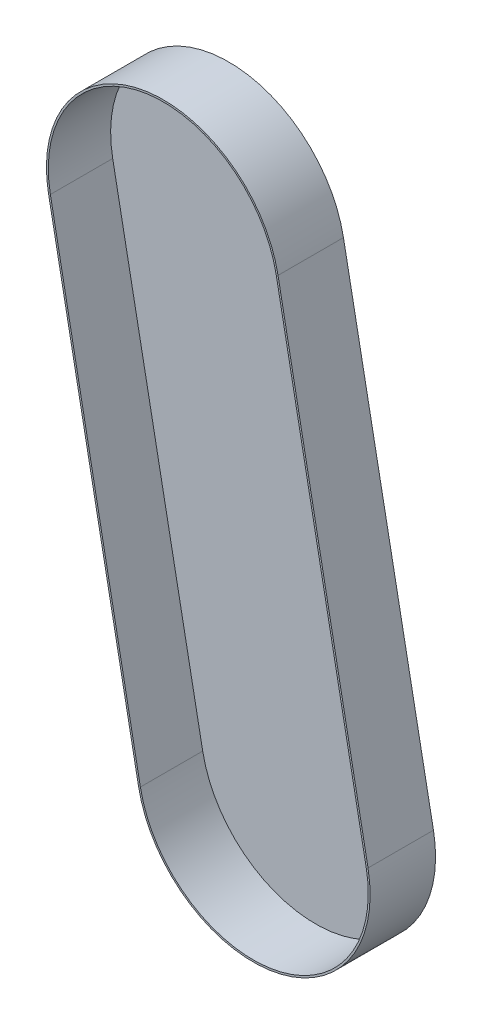
SolidWorks part; units mm, degrees
ref_plane "Front Plane" through (0, 0, 0) normal (0, 0, 1) x (1, 0, 0)
ref_plane "Top Plane" through (0, 0, 0) normal (0, 1, 0) x (1, 0, 0)
ref_plane "Right Plane" through (0, 0, 0) normal (1, 0, 0) x (0, 0, -1)
sketch "Sketch1" plane through (0, 0, 0) normal (0, 0, 1) x (1, 0, 0)
  line L0 (-24.7972, 233.6633) -> (32.9658, -66.856)
  line L1 (-172.1008, 205.3499) -> (-114.3378, -95.1694)
  arc A0 (-24.7972, 233.6633) -> (-172.1008, 205.3499) centre (-98.449, 219.5066) ccw
  arc A1 (-114.3378, -95.1694) -> (32.9658, -66.856) centre (-40.686, -81.0127) ccw
  dimension "D1" = 150
  dimension "D2" = 150
extrude "Boss-Extrude1" add sketch "Sketch1" along normal blind 2
sketch "Sketch2" plane through (0, 0, 2) normal (0, 0, 1) x (1, 0, 0)
  line L0 (-24.7972, 233.6633) -> (32.9658, -66.856)
  line L1 (-172.1008, 205.3499) -> (-114.3378, -95.1694)
  line L2 (-25.9756, 233.4368) -> (31.7874, -67.0826)
  line L3 (-170.9224, 205.5765) -> (-113.1594, -94.9429)
  arc A0 (-24.7972, 233.6633) -> (-172.1008, 205.3499) centre (-98.449, 219.5066) ccw
  arc A1 (-114.3378, -95.1694) -> (32.9658, -66.856) centre (-40.686, -81.0127) ccw
  arc A2 (-113.1594, -94.9429) -> (31.7874, -67.0826) centre (-40.686, -81.0127) ccw
  arc A3 (-25.9756, 233.4368) -> (-170.9224, 205.5765) centre (-98.449, 219.5066) ccw
  dimension "D1" = 150
  dimension "D2" = 150
  dimension "D3" = 1.2
extrude "Boss-Extrude2" add sketch "Sketch2" along normal blind 40
